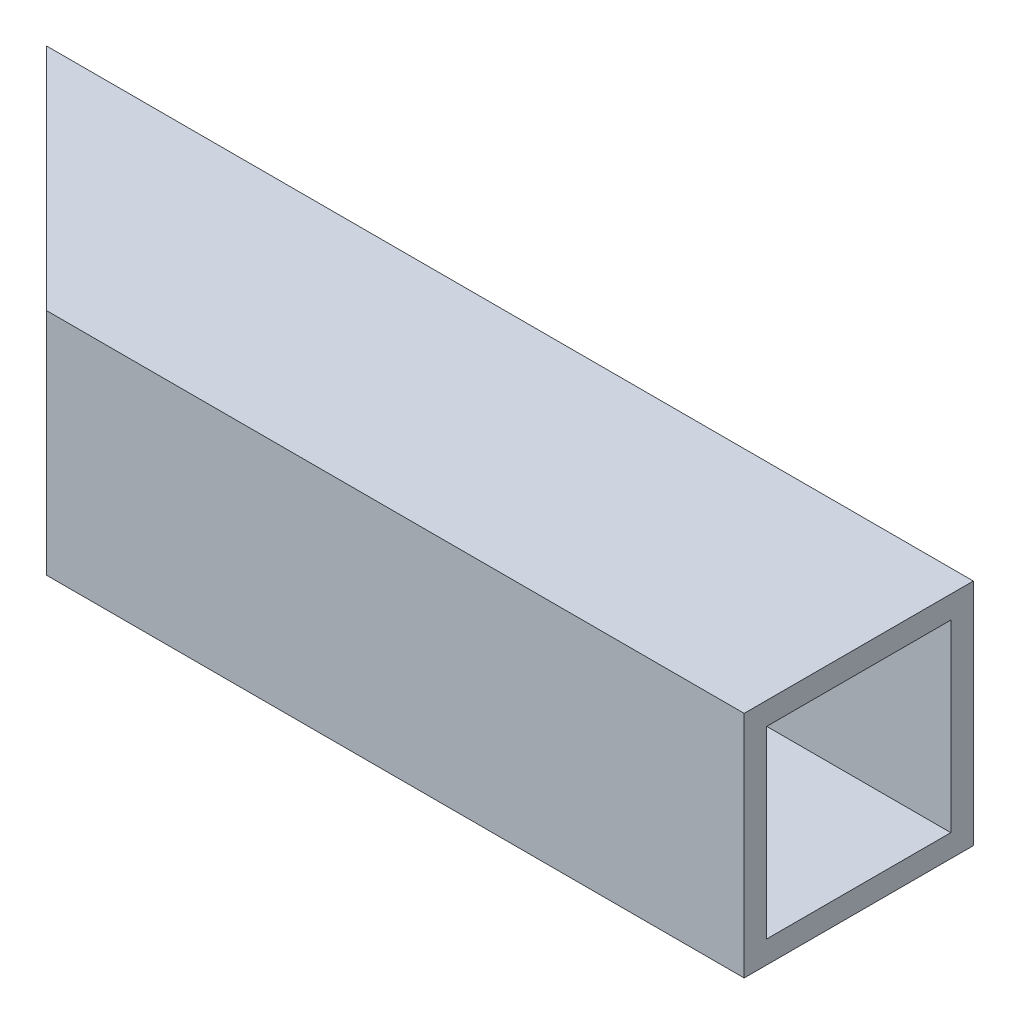
SolidWorks part; units mm, degrees
ref_plane "Front Plane" through (0, 0, 0) normal (0, 0, 1) x (1, 0, 0)
ref_plane "Top Plane" through (0, 0, 0) normal (0, 1, 0) x (1, 0, 0)
ref_plane "Right Plane" through (0, 0, 0) normal (1, 0, 0) x (0, 0, -1)
sketch "Sketch2" plane through (0, 0, 0) normal (1, 0, 0) x (0, 0, -1)
  line L1 (-12.7, 12.7) -> (12.7, 12.7)
  line L2 (-12.7, 12.7) -> (-12.7, -12.7)
  line L3 (-12.7, -12.7) -> (12.7, -12.7)
  line L4 (12.7, 12.7) -> (12.7, -12.7)
  line L5 (-12.7, 12.7) -> (12.7, -12.7) construction
  line L6 (-12.7, -12.7) -> (12.7, 12.7) construction
  line L7 (-10.2, 10.2) -> (10.2, 10.2)
  line L8 (-10.2, 10.2) -> (-10.2, -10.2)
  line L9 (-10.2, -10.2) -> (10.2, -10.2)
  line L10 (10.2, 10.2) -> (10.2, -10.2)
  line L11 (-10.2, 10.2) -> (10.2, -10.2) construction
  line L12 (-10.2, -10.2) -> (10.2, 10.2) construction
  point P0 (0, 0)
  point P6 (0, 0)
  dimension "D1" = 25.4
  dimension "D2" = 25.4
  dimension "D3" = 20.4
extrude "Boss-Extrude1" add sketch "Sketch2" along normal blind 102.7
sketch "Sketch3" plane through (0, 12.7, 0) normal (0, 1, 0) x (1, 0, 0)
  line L1 (102.7, -12.7) -> (0, -12.7) construction
  line L4 (0, -12.7) -> (0, 12.7)
  line L5 (0, 12.7) -> (25.4, -12.7)
  line L6 (25.4, -12.7) -> (0, -12.7)
  dimension "D2" = 45
extrude "Cut-Extrude1" cut sketch "Sketch3" against normal through all
